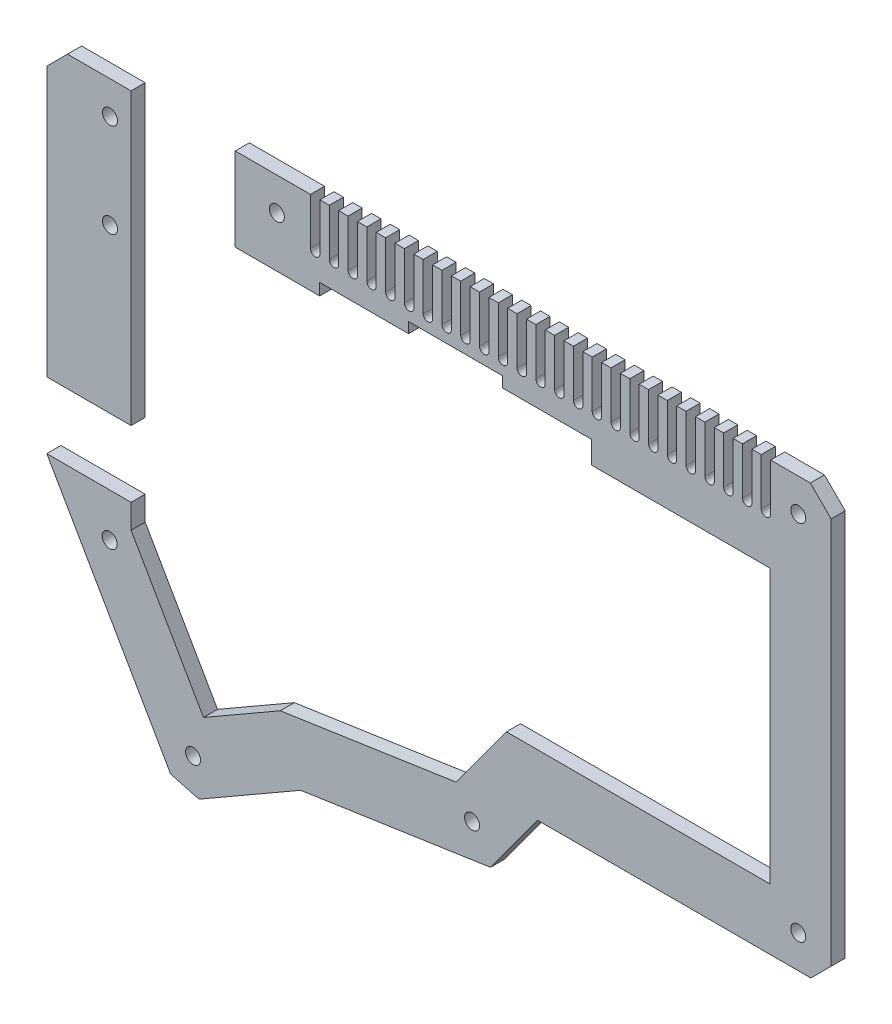
SolidWorks part; units mm, degrees
ref_plane "Plan de face" through (0, 0, 0) normal (0, 0, 1) x (1, 0, 0)
ref_plane "Plan de dessus" through (0, 0, 0) normal (0, 1, 0) x (1, 0, 0)
ref_plane "Plan de droite" through (0, 0, 0) normal (1, 0, 0) x (0, 0, -1)
sketch "Esquisse1" plane through (0, 0, 0) normal (0, 0, 1) x (1, 0, 0)
  line L0 (-117.3419, -15.4198) -> (-103.3409, -15.4198) construction
  line L1 (-103.3409, -15.4198) -> (-103.3409, -29.4208) construction
  line L2 (-103.3409, -29.4208) -> (-117.3419, -29.4208) construction
  line L3 (-117.3419, -29.4208) -> (-117.3419, -15.4198) construction
  line L4 (-98.3406, -27.0457) -> (-98.3406, -13.0447) construction
  line L5 (-98.3406, -13.0447) -> (-84.3396, -13.0447) construction
  line L6 (-84.3396, -13.0447) -> (-84.3396, -27.0457) construction
  line L7 (-84.3396, -27.0457) -> (-98.3406, -27.0457) construction
  line L8 (-79.3392, -24.6705) -> (-79.3392, -10.6695) construction
  line L9 (-79.3392, -10.6695) -> (-65.3382, -10.6695) construction
  line L10 (-65.3382, -10.6695) -> (-65.3382, -24.6705) construction
  line L11 (-65.3382, -24.6705) -> (-79.3392, -24.6705) construction
  line L12 (-60.3379, -27.0457) -> (-60.3379, -13.0447) construction
  line L13 (-60.3379, -13.0447) -> (-46.3369, -13.0447) construction
  line L14 (-46.3369, -13.0447) -> (-46.3369, -27.0457) construction
  line L15 (-46.3369, -27.0457) -> (-60.3379, -27.0457) construction
  line L16 (-41.3365, -31.796) -> (-41.3365, -17.795) construction
  line L17 (-41.3365, -17.795) -> (-27.3355, -17.795) construction
  line L18 (-27.3355, -17.795) -> (-27.3355, -31.796) construction
  line L19 (-27.3355, -31.796) -> (-41.3365, -31.796) construction
  line L20 (-22.3347, -31.796) -> (-22.3347, -17.795) construction
  line L21 (-22.3347, -17.795) -> (-8.3337, -17.795) construction
  line L22 (-8.3337, -17.795) -> (-8.3337, -31.796) construction
  line L23 (-8.3337, -31.796) -> (-22.3347, -31.796) construction
  line L24 (-117.3419, -34.4212) -> (-103.3409, -34.4212) construction
  line L25 (-103.3409, -34.4212) -> (-103.3409, -48.4222) construction
  line L26 (-103.3409, -48.4222) -> (-117.3419, -48.4222) construction
  line L27 (-117.3419, -48.4222) -> (-117.3419, -34.4212) construction
  line L28 (-98.3406, -32.046) -> (-84.3396, -32.046) construction
  line L29 (-84.3396, -32.046) -> (-84.3396, -46.047) construction
  line L30 (-84.3396, -46.047) -> (-98.3406, -46.047) construction
  line L31 (-98.3406, -46.047) -> (-98.3406, -32.046) construction
  line L32 (-79.3392, -29.6709) -> (-65.3382, -29.6709) construction
  line L33 (-65.3382, -29.6709) -> (-65.3382, -43.6718) construction
  line L34 (-65.3382, -43.6718) -> (-79.3392, -43.6718) construction
  line L35 (-79.3392, -43.6718) -> (-79.3392, -29.6709) construction
  line L36 (-60.3379, -32.046) -> (-46.3369, -32.046) construction
  line L37 (-46.3369, -32.046) -> (-46.3369, -46.047) construction
  line L38 (-46.3369, -46.047) -> (-60.3379, -46.047) construction
  line L39 (-60.3379, -46.047) -> (-60.3379, -32.046) construction
  line L40 (-41.3365, -36.7964) -> (-27.3355, -36.7964) construction
  line L41 (-27.3355, -36.7964) -> (-27.3355, -50.7973) construction
  line L42 (-27.3355, -50.7973) -> (-41.3365, -50.7973) construction
  line L43 (-41.3365, -50.7973) -> (-41.3365, -36.7964) construction
  line L44 (-22.3347, -36.7964) -> (-8.3337, -36.7964) construction
  line L45 (-8.3337, -36.7964) -> (-8.3337, -50.7973) construction
  line L46 (-8.3337, -50.7973) -> (-22.3347, -50.7973) construction
  line L47 (-22.3347, -50.7973) -> (-22.3347, -36.7964) construction
  line L48 (-22.3347, -55.7977) -> (-8.3337, -55.7977) construction
  line L49 (-8.3337, -55.7977) -> (-8.3337, -69.7987) construction
  line L50 (-8.3337, -69.7987) -> (-22.3347, -69.7987) construction
  line L51 (-22.3347, -69.7987) -> (-22.3347, -55.7977) construction
  line L52 (-41.3365, -55.7977) -> (-27.3355, -55.7977) construction
  line L53 (-27.3355, -55.7977) -> (-27.3355, -69.7987) construction
  line L54 (-27.3355, -69.7987) -> (-41.3365, -69.7987) construction
  line L55 (-41.3365, -69.7987) -> (-41.3365, -55.7977) construction
  line L56 (-60.3379, -51.0474) -> (-46.3369, -51.0474) construction
  line L57 (-46.3369, -51.0474) -> (-46.3369, -65.0484) construction
  line L58 (-46.3369, -65.0484) -> (-60.3379, -65.0484) construction
  line L59 (-60.3379, -65.0484) -> (-60.3379, -51.0474) construction
  line L60 (-79.3392, -48.6722) -> (-65.3382, -48.6722) construction
  line L61 (-65.3382, -48.6722) -> (-65.3382, -62.6732) construction
  line L62 (-65.3382, -62.6732) -> (-79.3392, -62.6732) construction
  line L63 (-79.3392, -62.6732) -> (-79.3392, -48.6722) construction
  line L64 (-98.3406, -51.0474) -> (-84.3396, -51.0474) construction
  line L65 (-84.3396, -51.0474) -> (-84.3396, -65.0484) construction
  line L66 (-84.3396, -65.0484) -> (-98.3406, -65.0484) construction
  line L67 (-98.3406, -65.0484) -> (-98.3406, -51.0474) construction
  line L68 (-117.3419, -53.4225) -> (-103.3409, -53.4225) construction
  line L69 (-103.3409, -53.4225) -> (-103.3409, -67.4235) construction
  line L70 (-103.3409, -67.4235) -> (-117.3419, -67.4235) construction
  line L71 (-117.3419, -67.4235) -> (-117.3419, -53.4225) construction
  line L72 (-88.8399, -70.6738) -> (-74.8389, -70.6738) construction
  line L73 (-74.8389, -70.6738) -> (-74.8389, -84.6747) construction
  line L74 (-74.8389, -84.6747) -> (-88.8399, -84.6747) construction
  line L75 (-88.8399, -84.6747) -> (-88.8399, -70.6738) construction
  line L76 (-111.4175, -75.4665) -> (-97.8899, -71.8565) construction
  line L77 (-97.8899, -71.8565) -> (-94.28, -85.3841) construction
  line L78 (-94.28, -85.3841) -> (-107.8075, -88.9941) construction
  line L79 (-107.8075, -88.9941) -> (-111.4175, -75.4665) construction
  line L80 (-134.6581, -81.5997) -> (-122.5281, -74.6075) construction
  line L81 (-122.5281, -74.6075) -> (-115.5359, -86.7375) construction
  line L82 (-115.5359, -86.7375) -> (-127.6659, -93.7297) construction
  line L83 (-127.6659, -93.7297) -> (-134.6581, -81.5997) construction
  line L86 (-6.4297, -71.9336) -> (-62.0853, -71.9336) construction
  line L89 (-72.824, -86.6446) -> (-62.0853, -71.9336) construction
  line L96 (-109.7697, -91.4639) -> (-73.0906, -86.6918) construction
  line L97 (-124.664, -99.8297) -> (-110.3971, -91.5881) construction
  line L98 (-139.9408, -76.5013) -> (-126.7151, -99.4281) construction
  line L99 (-119.8527, -15.5421) -> (-139.6028, -15.5421) construction
  line L100 (-100.8528, -13.2921) -> (-118.8527, -13.2921) construction
  line L101 (-63.8455, -8.5421) -> (-80.8528, -8.5421) construction
  line L102 (-44.8455, -10.792) -> (-62.8485, -10.792) construction
  line L103 (-25.8456, -15.5421) -> (-43.8486, -15.5421) construction
  line L104 (-6.8456, -15.5421) -> (-23.8529, -15.5421) construction
  line L105 (-6.2741, -71.3672) -> (-6.2741, -16.1136) construction
  line L106 (-23.8529, -71.9423) -> (-6.8456, -71.9423) construction
  line L107 (-61.8455, -71.9423) -> (-25.8456, -71.9423) construction
  line L108 (-72.6738, -86.4911) -> (-62.1363, -72.0583) construction
  line L109 (-140.1743, -16.1136) -> (-140.1743, -75.5958) construction
  line L110 (-134.3462, 1.5705) -> (-134.3466, -55.7217) construction
  line L111 (-134.3466, -55.7217) -> (-160.479, -70.8411) construction
  line L112 (-160.479, -70.8411) -> (-133.7613, -117.344) construction
  line L113 (-126.937, -119.1852) -> (-105.0783, -106.604) construction
  line L114 (-105.0783, -106.604) -> (-64.4097, -100.5586) construction
  line L115 (-64.4097, -100.5586) -> (-54.4636, -86.9336) construction
  line L116 (3.6609, -86.9336) -> (-54.4636, -86.9336) construction
  line L117 (8.5703, -82.0242) -> (8.5703, 1.315) construction
  line L129 (8.5703, -86.9336) -> (8.5703, -0.6796) construction
  line L130 (-48.4337, 6.3182) -> (-96.435, 6.3209) construction
  line L131 (-115.3458, 1.5705) -> (-134.3462, 1.5705) construction
  line L132 (-160.479, -3.4295) -> (-160.479, -70.8411) construction
  line L134 (-119.3463, 1.5705) -> (-119.3464, -12.4295)
  line L135 (-119.3466, -64.3728) -> (-135.695, -73.8315) construction
  line L136 (-140.0228, -76.3355) -> (-140.0228, -76.3321)
  line L138 (-160.479, -70.8411) -> (-131.2704, -121.6794) construction
  line L139 (-131.2704, -121.6794) -> (-105.0783, -106.604) construction
  line L140 (-133.7613, -117.344) -> (-126.937, -119.1852) construction
  line L142 (8.5703, 1.315) -> (3.5703, 6.3153) construction
  line L143 (8.5703, -86.9336) -> (-54.4636, -86.9336) construction
  line L144 (8.5703, -82.0242) -> (3.6609, -86.9336) construction
  line L150 (-140.0228, 1.5705) -> (-140.0228, 6.3209) construction
  line L151 (-140.0228, 6.3209) -> (-155.479, 6.3209) construction
  line L152 (-160.479, 1.3209) -> (-160.479, -3.4295) construction
  line L153 (-155.479, 6.3209) -> (-160.479, 1.3209) construction
  line L154 (-103.4315, 5.3209) -> (-118.3463, 5.3209) construction
  line L155 (-146.0924, -79.8227) -> (-128.3223, -110.752) construction
  line L156 (-128.3223, -110.752) -> (-107.7547, -98.9139) construction
  line L157 (-140.0228, -78.3428) -> (-126.1111, -102.5565)
  line L158 (-126.1111, -102.5565) -> (-109.762, -93.1464)
  line L159 (-109.762, -93.1464) -> (-72.2631, -87.5722)
  line L160 (-72.2631, -87.5722) -> (-61.5772, -72.9336)
  line L161 (-5.4297, -72.9336) -> (-61.5772, -72.9336)
  line L162 (-5.4297, -72.9336) -> (-5.4297, -14.6796)
  line L163 (-5.4297, -14.6796) -> (-43.4324, -14.6796)
  line L164 (-43.4324, -14.6796) -> (-43.4324, -9.9293)
  line L165 (-43.4324, -9.9293) -> (-62.4337, -9.9293)
  line L166 (-62.4337, -9.9293) -> (-62.4337, -7.681)
  line L167 (-62.4337, -7.681) -> (-82.435, -7.6799)
  line L168 (-82.435, -7.6799) -> (-82.435, -9.9293)
  line L169 (-82.435, -9.9293) -> (-101.3458, -9.9293)
  line L170 (-101.3458, -9.9293) -> (-101.3458, -12.4295)
  line L171 (-101.3458, -12.4295) -> (-119.3464, -12.4295)
  line L172 (-120.3463, -12.4295) -> (-120.3466, -64.3728) construction
  line L173 (-119.8474, -63.5072) -> (-140.5236, -75.4699) construction
  line L174 (-107.7547, -98.9139) -> (-68.8973, -93.1378) construction
  line L175 (-68.8973, -93.1378) -> (-58.5285, -78.9336) construction
  line L176 (0.5703, -78.9336) -> (-58.5285, -78.9336) construction
  line L177 (0.5703, -78.9336) -> (0.5703, -1.6845) construction
  line L178 (3.1505, 5.3209) -> (-119.3463, 5.3209)
  line L179 (0.5703, -78.9336) -> (0.5703, -14.6796) construction
  line L180 (-146.0228, -76.3355) -> (-146.0228, 1.5705) construction
  line L181 (-140.0228, -76.3355) -> (-140.0228, 1.5705) construction
  line L182 (-135.695, -73.8315) -> (-140.0228, -71.3355) construction
  line L186 (-118.3463, 5.3209) -> (-118.3463, 1.5705) construction
  line L187 (-118.3463, 1.5705) -> (-118.3466, -64.9495) construction
  line L188 (-118.3466, -64.9495) -> (-135.6942, -74.9864) construction
  line L189 (-135.6942, -74.9864) -> (-141.0228, -71.9131) construction
  line L190 (-141.0228, -71.9131) -> (-141.0228, 1.5705) construction
  line L191 (-141.0228, 1.5705) -> (-141.0228, 5.3209) construction
  line L192 (-141.5228, 5.3209) -> (-155.0648, 5.3209)
  line L193 (-155.0648, 5.3209) -> (-159.479, 0.9066)
  line L194 (-159.479, 0.9066) -> (-159.479, -3.4295)
  line L195 (-159.479, -3.4295) -> (-159.479, -70.5743)
  line L196 (-159.479, -70.5743) -> (-133.1007, -116.4865)
  line L197 (-133.1007, -116.4865) -> (-127.0766, -118.1118)
  line L198 (-127.0766, -118.1118) -> (-105.4129, -105.6427)
  line L199 (-105.4129, -105.6427) -> (-64.9706, -99.631)
  line L200 (-64.9706, -99.631) -> (-54.9717, -85.9336)
  line L201 (3.2467, -85.9336) -> (-54.9717, -85.9336)
  line L202 (7.5703, -81.61) -> (3.2467, -85.9336)
  line L203 (7.5703, -81.61) -> (7.5703, 0.9008)
  line L204 (7.5703, 0.9008) -> (3.1505, 5.3209)
  line L206 (-140.0228, -76.3321) -> (-119.3466, -64.3728) construction
  line L207 (-140.0228, -71.3355) -> (-140.0228, 1.5705) construction
  line L208 (-119.3463, 5.3209) -> (-119.3463, 1.5705)
  line L209 (-140.8899, -76.8336) -> (-126.1111, -102.5565) construction
  line L210 (-119.3463, 1.5705) -> (-119.3466, -64.3728) construction
  line L211 (-101.3458, -12.4295) -> (-120.3463, -12.4295) construction
  line L212 (-119.3463, 6.3209) -> (-119.3463, 1.5705) construction
  line L217 (-6.4297, -71.9336) -> (-6.4297, -15.6796) construction
  line L220 (-6.4297, -15.6796) -> (-44.4324, -15.6796) construction
  line L221 (-44.4324, -15.6796) -> (-44.4324, -10.9293) construction
  line L222 (-44.4324, -10.9293) -> (-63.4337, -10.9293) construction
  line L223 (-63.4337, -10.9293) -> (-63.4337, -8.681) construction
  line L224 (-63.4337, -8.681) -> (-81.435, -8.68) construction
  line L225 (-81.435, -8.68) -> (-81.435, -10.9293) construction
  line L226 (-81.435, -10.9293) -> (-100.3458, -10.9293) construction
  line L227 (-100.3458, -10.9293) -> (-100.3458, -13.4295) construction
  line L228 (-100.3458, -13.4295) -> (-119.3463, -13.4295) construction
  line L231 (-119.3463, -13.4295) -> (-119.3466, -64.3728) construction
  line L232 (-119.3466, -64.3728) -> (-140.0228, -76.3355) construction
  line L233 (-140.0228, -76.3355) -> (-125.7426, -101.1906) construction
  line L234 (-125.7426, -101.1906) -> (-110.0965, -92.1851) construction
  line L235 (-110.0965, -92.1851) -> (-72.824, -86.6446) construction
  line L237 (7.5703, 0.9008) -> (3.1561, 5.3153) construction
  line L238 (-140.0228, -76.3355) -> (-140.8899, -76.8336) construction
  line L241 (-140.8899, -76.8336) -> (-140.0228, -78.3428)
  line L244 (-140.521, -75.4684) -> (-140.5223, -75.4691)
  line L247 (-141.5228, -75.732) -> (-140.8899, -76.8336)
  line L253 (-140.0228, -75.1802) -> (-140.0228, 5.3209) construction
  line L256 (-146.0228, -1.6779) -> (-146.0228, -21.6805) construction
  line L259 (-141.5228, -75.1802) -> (-141.5228, 5.3209)
  line L262 (-141.5228, -75.1802) -> (-141.5228, -75.732)
  line L265 (-141.0228, 5.3209) -> (-155.0648, 5.3209) construction
  line L271 (-140.521, -75.4684) -> (-141.3881, -75.9666) construction
  line L321 (3.1561, 5.3153) -> (-96.435, 5.3209) construction
  line L328 (-48.4337, 4.0707) -> (-48.4337, 6.3182) construction
  line L329 (-29.4324, 4.0707) -> (-48.4337, 4.0707) construction
  line L330 (-29.4324, -0.6796) -> (-29.4324, 4.0707) construction
  line L331 (8.5703, -0.6796) -> (-29.4324, -0.6796) construction
  line L332 (-115.3458, 4.0707) -> (-115.3458, 1.5705) construction
  line L333 (-96.435, 4.0707) -> (-115.3458, 4.0707) construction
  line L334 (-96.435, 6.3209) -> (-96.435, 4.0707) construction
  line L368 (-103.4315, 5.3209) -> (-96.435, 5.3209) construction
  line L386 (3.5703, 6.3153) -> (-96.435, 6.3209) construction
  line L438 (-103.4315, 6.3209) -> (-96.435, 6.3209) construction
  line L439 (-103.4315, 6.3209) -> (-119.3463, 6.3209) construction
  circle A2 centre (0.5703, -1.6845) radius 1.6
  circle A3 centre (0.5703, -1.6845) radius 3 construction
  circle A4 centre (-110.4876, -1.6784) radius 1.6
  circle A5 centre (0.5703, -78.9336) radius 1.6
  circle A6 centre (-68.8973, -93.1378) radius 1.6
  circle A7 centre (-128.3223, -110.752) radius 1.6
  circle A8 centre (-146.0924, -79.8227) radius 1.6
  circle A9 centre (-146.0228, -1.6779) radius 1.6
  circle A10 centre (-110.4876, -1.6784) radius 3 construction
  circle A11 centre (-146.0228, -1.6779) radius 3 construction
  circle A12 centre (-146.0924, -79.8227) radius 3 construction
  circle A13 centre (-128.3223, -110.752) radius 3 construction
  circle A14 centre (-68.8973, -93.1378) radius 3 construction
  circle A15 centre (0.5703, -78.9336) radius 3 construction
  circle A16 centre (-146.0228, -21.6805) radius 1.6
  point P138 (-160.479, 1.5705)
  point P139 (8.5703, 6.315)
  point P150 (-160.479, 6.3209)
  dimension "D3" = 3.2
  dimension "D4" = 6
  dimension "D6" = 3.2
  dimension "D7" = 3.2
  dimension "D8" = 3.2
  dimension "D9" = 3.2
  dimension "D10" = 3.2
  dimension "D15" = 3.2
  dimension "D2" = 1
  dimension "D1" = 15
  dimension "D5" = 1
  dimension "D13" = 6
  dimension "D16" = 1.5
extrude "Boss.-Extru.1" add sketch "Esquisse1" along normal blind 3
sketch "Esquisse2" plane through (0, 0, 3) normal (0, 0, 1) x (1, 0, 0)
  line L0 (7.5703, -7.8762) -> (-6.3155, -7.8762) construction
  line L1 (7.5703, -81.61) -> (7.5703, 0.9008) construction
  line L2 (-6.3155, 5.3209) -> (-6.3155, -4.6791) construction
  line L3 (3.1505, 5.3209) -> (-119.3463, 5.3209) construction
  line L4 (-6.3155, 8.6159) -> (-6.3155, -4.6791) construction
  line L5 (-5.3155, 8.6159) -> (-5.3155, -4.6791)
  line L6 (-7.3155, 8.6159) -> (-7.3155, -4.6791)
  line L7 (-10.3155, 8.6159) -> (-10.3155, -4.6791) construction
  line L8 (-9.3155, 8.6159) -> (-9.3155, -4.6791)
  line L9 (-11.3155, 8.6159) -> (-11.3155, -4.6791)
  line L10 (-14.3155, 8.6159) -> (-14.3155, -4.6791) construction
  line L11 (-13.3155, 8.6159) -> (-13.3155, -4.6791)
  line L12 (-15.3155, 8.6159) -> (-15.3155, -4.6791)
  line L13 (-18.3155, 8.6159) -> (-18.3155, -4.6791) construction
  line L14 (-17.3155, 8.6159) -> (-17.3155, -4.6791)
  line L15 (-19.3155, 8.6159) -> (-19.3155, -4.6791)
  line L16 (-22.3155, 8.6159) -> (-22.3155, -4.6791) construction
  line L17 (-21.3155, 8.6159) -> (-21.3155, -4.6791)
  line L18 (-23.3155, 8.6159) -> (-23.3155, -4.6791)
  line L19 (-26.3155, 8.6159) -> (-26.3155, -4.6791) construction
  line L20 (-25.3155, 8.6159) -> (-25.3155, -4.6791)
  line L21 (-27.3155, 8.6159) -> (-27.3155, -4.6791)
  line L22 (-30.3155, 8.6159) -> (-30.3155, -4.6791) construction
  line L23 (-29.3155, 8.6159) -> (-29.3155, -4.6791)
  line L24 (-31.3155, 8.6159) -> (-31.3155, -4.6791)
  line L25 (-34.3155, 8.6159) -> (-34.3155, -4.6791) construction
  line L26 (-33.3155, 8.6159) -> (-33.3155, -4.6791)
  line L27 (-35.3155, 8.6159) -> (-35.3155, -4.6791)
  line L28 (-38.3155, 8.6159) -> (-38.3155, -4.6791) construction
  line L29 (-37.3155, 8.6159) -> (-37.3155, -4.6791)
  line L30 (-39.3155, 8.6159) -> (-39.3155, -4.6791)
  line L31 (-42.3155, 8.6159) -> (-42.3155, -4.6791) construction
  line L32 (-41.3155, 8.6159) -> (-41.3155, -4.6791)
  line L33 (-43.3155, 8.6159) -> (-43.3155, -4.6791)
  line L34 (-46.3155, 8.6159) -> (-46.3155, -4.6791) construction
  line L35 (-45.3155, 8.6159) -> (-45.3155, -4.6791)
  line L36 (-47.3155, 8.6159) -> (-47.3155, -4.6791)
  line L37 (-50.3155, 8.6159) -> (-50.3155, -4.6791) construction
  line L38 (-49.3155, 8.6159) -> (-49.3155, -4.6791)
  line L39 (-51.3155, 8.6159) -> (-51.3155, -4.6791)
  line L40 (-54.3155, 8.6159) -> (-54.3155, -4.6791) construction
  line L41 (-53.3155, 8.6159) -> (-53.3155, -4.6791)
  line L42 (-55.3155, 8.6159) -> (-55.3155, -4.6791)
  line L43 (-58.3155, 8.6159) -> (-58.3155, -4.6791) construction
  line L44 (-57.3155, 8.6159) -> (-57.3155, -4.6791)
  line L45 (-59.3155, 8.6159) -> (-59.3155, -4.6791)
  line L46 (-62.3155, 8.6159) -> (-62.3155, -4.6791) construction
  line L47 (-61.3155, 8.6159) -> (-61.3155, -4.6791)
  line L48 (-63.3155, 8.6159) -> (-63.3155, -4.6791)
  line L49 (-66.3155, 8.6159) -> (-66.3155, -4.6791) construction
  line L50 (-65.3155, 8.6159) -> (-65.3155, -4.6791)
  line L51 (-67.3155, 8.6159) -> (-67.3155, -4.6791)
  line L52 (-70.3155, 8.6159) -> (-70.3155, -4.6791) construction
  line L53 (-69.3155, 8.6159) -> (-69.3155, -4.6791)
  line L54 (-71.3155, 8.6159) -> (-71.3155, -4.6791)
  line L55 (-74.3155, 8.6159) -> (-74.3155, -4.6791) construction
  line L56 (-73.3155, 8.6159) -> (-73.3155, -4.6791)
  line L57 (-75.3155, 8.6159) -> (-75.3155, -4.6791)
  line L58 (-78.3155, 8.6159) -> (-78.3155, -4.6791) construction
  line L59 (-77.3155, 8.6159) -> (-77.3155, -4.6791)
  line L60 (-79.3155, 8.6159) -> (-79.3155, -4.6791)
  line L61 (-82.3155, 8.6159) -> (-82.3155, -4.6791) construction
  line L62 (-81.3155, 8.6159) -> (-81.3155, -4.6791)
  line L63 (-83.3155, 8.6159) -> (-83.3155, -4.6791)
  line L64 (-86.3155, 8.6159) -> (-86.3155, -4.6791) construction
  line L65 (-85.3155, 8.6159) -> (-85.3155, -4.6791)
  line L66 (-87.3155, 8.6159) -> (-87.3155, -4.6791)
  line L67 (-90.3155, 8.6159) -> (-90.3155, -4.6791) construction
  line L68 (-89.3155, 8.6159) -> (-89.3155, -4.6791)
  line L69 (-91.3155, 8.6159) -> (-91.3155, -4.6791)
  line L70 (-94.3155, 8.6159) -> (-94.3155, -4.6791) construction
  line L71 (-93.3155, 8.6159) -> (-93.3155, -4.6791)
  line L72 (-95.3155, 8.6159) -> (-95.3155, -4.6791)
  line L73 (-98.3155, 8.6159) -> (-98.3155, -4.6791) construction
  line L74 (-97.3155, 8.6159) -> (-97.3155, -4.6791)
  line L75 (-99.3155, 8.6159) -> (-99.3155, -4.6791)
  line L76 (-102.3155, 8.6159) -> (-102.3155, -4.6791) construction
  line L77 (-101.3155, 8.6159) -> (-101.3155, -4.6791)
  line L78 (-103.3155, 8.6159) -> (-103.3155, -4.6791)
  arc A0 (-5.3155, 8.6159) -> (-7.3155, 8.6159) centre (-6.3155, 8.6159) ccw
  arc A1 (-7.3155, -4.6791) -> (-5.3155, -4.6791) centre (-6.3155, -4.6791) ccw
  arc A2 (-9.3155, 8.6159) -> (-11.3155, 8.6159) centre (-10.3155, 8.6159) ccw
  arc A3 (-11.3155, -4.6791) -> (-9.3155, -4.6791) centre (-10.3155, -4.6791) ccw
  arc A4 (-13.3155, 8.6159) -> (-15.3155, 8.6159) centre (-14.3155, 8.6159) ccw
  arc A5 (-15.3155, -4.6791) -> (-13.3155, -4.6791) centre (-14.3155, -4.6791) ccw
  arc A6 (-17.3155, 8.6159) -> (-19.3155, 8.6159) centre (-18.3155, 8.6159) ccw
  arc A7 (-19.3155, -4.6791) -> (-17.3155, -4.6791) centre (-18.3155, -4.6791) ccw
  arc A8 (-21.3155, 8.6159) -> (-23.3155, 8.6159) centre (-22.3155, 8.6159) ccw
  arc A9 (-23.3155, -4.6791) -> (-21.3155, -4.6791) centre (-22.3155, -4.6791) ccw
  arc A10 (-25.3155, 8.6159) -> (-27.3155, 8.6159) centre (-26.3155, 8.6159) ccw
  arc A11 (-27.3155, -4.6791) -> (-25.3155, -4.6791) centre (-26.3155, -4.6791) ccw
  arc A12 (-29.3155, 8.6159) -> (-31.3155, 8.6159) centre (-30.3155, 8.6159) ccw
  arc A13 (-31.3155, -4.6791) -> (-29.3155, -4.6791) centre (-30.3155, -4.6791) ccw
  arc A14 (-33.3155, 8.6159) -> (-35.3155, 8.6159) centre (-34.3155, 8.6159) ccw
  arc A15 (-35.3155, -4.6791) -> (-33.3155, -4.6791) centre (-34.3155, -4.6791) ccw
  arc A16 (-37.3155, 8.6159) -> (-39.3155, 8.6159) centre (-38.3155, 8.6159) ccw
  arc A17 (-39.3155, -4.6791) -> (-37.3155, -4.6791) centre (-38.3155, -4.6791) ccw
  arc A18 (-41.3155, 8.6159) -> (-43.3155, 8.6159) centre (-42.3155, 8.6159) ccw
  arc A19 (-43.3155, -4.6791) -> (-41.3155, -4.6791) centre (-42.3155, -4.6791) ccw
  arc A20 (-45.3155, 8.6159) -> (-47.3155, 8.6159) centre (-46.3155, 8.6159) ccw
  arc A21 (-47.3155, -4.6791) -> (-45.3155, -4.6791) centre (-46.3155, -4.6791) ccw
  arc A22 (-49.3155, 8.6159) -> (-51.3155, 8.6159) centre (-50.3155, 8.6159) ccw
  arc A23 (-51.3155, -4.6791) -> (-49.3155, -4.6791) centre (-50.3155, -4.6791) ccw
  arc A24 (-53.3155, 8.6159) -> (-55.3155, 8.6159) centre (-54.3155, 8.6159) ccw
  arc A25 (-55.3155, -4.6791) -> (-53.3155, -4.6791) centre (-54.3155, -4.6791) ccw
  arc A26 (-57.3155, 8.6159) -> (-59.3155, 8.6159) centre (-58.3155, 8.6159) ccw
  arc A27 (-59.3155, -4.6791) -> (-57.3155, -4.6791) centre (-58.3155, -4.6791) ccw
  arc A28 (-61.3155, 8.6159) -> (-63.3155, 8.6159) centre (-62.3155, 8.6159) ccw
  arc A29 (-63.3155, -4.6791) -> (-61.3155, -4.6791) centre (-62.3155, -4.6791) ccw
  arc A30 (-65.3155, 8.6159) -> (-67.3155, 8.6159) centre (-66.3155, 8.6159) ccw
  arc A31 (-67.3155, -4.6791) -> (-65.3155, -4.6791) centre (-66.3155, -4.6791) ccw
  arc A32 (-69.3155, 8.6159) -> (-71.3155, 8.6159) centre (-70.3155, 8.6159) ccw
  arc A33 (-71.3155, -4.6791) -> (-69.3155, -4.6791) centre (-70.3155, -4.6791) ccw
  arc A34 (-73.3155, 8.6159) -> (-75.3155, 8.6159) centre (-74.3155, 8.6159) ccw
  arc A35 (-75.3155, -4.6791) -> (-73.3155, -4.6791) centre (-74.3155, -4.6791) ccw
  arc A36 (-77.3155, 8.6159) -> (-79.3155, 8.6159) centre (-78.3155, 8.6159) ccw
  arc A37 (-79.3155, -4.6791) -> (-77.3155, -4.6791) centre (-78.3155, -4.6791) ccw
  arc A38 (-81.3155, 8.6159) -> (-83.3155, 8.6159) centre (-82.3155, 8.6159) ccw
  arc A39 (-83.3155, -4.6791) -> (-81.3155, -4.6791) centre (-82.3155, -4.6791) ccw
  arc A40 (-85.3155, 8.6159) -> (-87.3155, 8.6159) centre (-86.3155, 8.6159) ccw
  arc A41 (-87.3155, -4.6791) -> (-85.3155, -4.6791) centre (-86.3155, -4.6791) ccw
  arc A42 (-89.3155, 8.6159) -> (-91.3155, 8.6159) centre (-90.3155, 8.6159) ccw
  arc A43 (-91.3155, -4.6791) -> (-89.3155, -4.6791) centre (-90.3155, -4.6791) ccw
  arc A44 (-93.3155, 8.6159) -> (-95.3155, 8.6159) centre (-94.3155, 8.6159) ccw
  arc A45 (-95.3155, -4.6791) -> (-93.3155, -4.6791) centre (-94.3155, -4.6791) ccw
  arc A46 (-97.3155, 8.6159) -> (-99.3155, 8.6159) centre (-98.3155, 8.6159) ccw
  arc A47 (-99.3155, -4.6791) -> (-97.3155, -4.6791) centre (-98.3155, -4.6791) ccw
  arc A48 (-101.3155, 8.6159) -> (-103.3155, 8.6159) centre (-102.3155, 8.6159) ccw
  arc A49 (-103.3155, -4.6791) -> (-101.3155, -4.6791) centre (-102.3155, -4.6791) ccw
  point P9 (-6.3155, 1.9684)
  point P17 (-10.3155, 1.9684)
  point P24 (-14.3155, 1.9684)
  point P31 (-18.3155, 1.9684)
  point P38 (-22.3155, 1.9684)
  point P45 (-26.3155, 1.9684)
  point P52 (-30.3155, 1.9684)
  point P59 (-34.3155, 1.9684)
  point P66 (-38.3155, 1.9684)
  point P73 (-42.3155, 1.9684)
  point P80 (-46.3155, 1.9684)
  point P87 (-50.3155, 1.9684)
  point P94 (-54.3155, 1.9684)
  point P101 (-58.3155, 1.9684)
  point P108 (-62.3155, 1.9684)
  point P115 (-66.3155, 1.9684)
  point P122 (-70.3155, 1.9684)
  point P129 (-74.3155, 1.9684)
  point P136 (-78.3155, 1.9684)
  point P143 (-82.3155, 1.9684)
  point P150 (-86.3155, 1.9684)
  point P157 (-90.3155, 1.9684)
  point P164 (-94.3155, 1.9684)
  point P171 (-98.3155, 1.9684)
  point P178 (-102.3155, 1.9684)
  dimension "D1" = 25
extrude "Enlèv. mat.-Extru.1" cut sketch "Esquisse2" against normal blind 10
sketch "Esquisse3" plane through (0, 0, 3) normal (0, 0, 1) x (1, 0, 0)
  line L0 (-159.479, -70.5743) -> (-140.0228, -70.5743)
  line L1 (-140.0228, -75.1802) -> (-140.0228, 5.3209) construction
  line L2 (-117.3419, -53.4225) -> (-140.0228, -53.4225) construction
  line L3 (-140.0228, -53.4225) -> (-140.0228, -56.4239) construction
  line L4 (-140.0228, -70.5743) -> (-140.0228, -56.4239)
  line L5 (-140.0228, -56.4239) -> (-159.479, -56.4239)
  line L6 (-159.479, -3.4295) -> (-159.479, -70.5743) construction
  line L7 (-159.479, -56.4239) -> (-159.479, -70.5743)
extrude "Enlèv. mat.-Extru.2" cut sketch "Esquisse3" against normal blind 10
sketch "Esquisse4" plane through (0, 0, 3) normal (0, 0, 1) x (1, 0, 0)
  line L5 (-159.479, -56.4239) -> (-141.5228, -56.4239)
  line L6 (-141.5228, -56.4239) -> (-141.5228, 5.3209)
  line L7 (-141.5228, 5.3209) -> (-155.0648, 5.3209)
  line L8 (-155.0648, 5.3209) -> (-159.479, 0.9066)
  line L9 (-159.479, 0.9066) -> (-159.479, -56.4239)
  line L10 (-159.479, -56.4239) -> (-141.5228, -56.4239)
  line L11 (-141.5228, -56.4239) -> (-141.5228, 5.3209)
  line L12 (-141.5228, 5.3209) -> (-155.0648, 5.3209)
  line L13 (-155.0648, 5.3209) -> (-159.479, 0.9066)
  line L14 (-159.479, 0.9066) -> (-159.479, -56.4239)
  line L104 (-141.5228, -70.5743) -> (-159.479, -70.5743)
  line L105 (-159.479, -70.5743) -> (-133.1007, -116.4865)
  line L106 (-133.1007, -116.4865) -> (-127.0766, -118.1118)
  line L107 (-127.0766, -118.1118) -> (-105.4129, -105.6427)
  line L108 (-105.4129, -105.6427) -> (-64.9706, -99.631)
  line L109 (-64.9706, -99.631) -> (-54.9717, -85.9336)
  line L110 (-54.9717, -85.9336) -> (3.2467, -85.9336)
  line L111 (3.2467, -85.9336) -> (7.5703, -81.61)
  line L112 (7.5703, -81.61) -> (7.5703, 0.9008)
  line L113 (7.5703, 0.9008) -> (3.1505, 5.3209)
  line L114 (3.1505, 5.3209) -> (-5.3155, 5.3209)
  line L115 (-5.3155, 5.3209) -> (-5.3155, -4.6791)
  line L116 (-7.3155, -4.6791) -> (-7.3155, 5.3209)
  line L117 (-7.3155, 5.3209) -> (-9.3155, 5.3209)
  line L118 (-9.3155, 5.3209) -> (-9.3155, -4.6791)
  line L119 (-11.3155, -4.6791) -> (-11.3155, 5.3209)
  line L120 (-11.3155, 5.3209) -> (-13.3155, 5.3209)
  line L121 (-13.3155, 5.3209) -> (-13.3155, -4.6791)
  line L122 (-15.3155, -4.6791) -> (-15.3155, 5.3209)
  line L123 (-15.3155, 5.3209) -> (-17.3155, 5.3209)
  line L124 (-17.3155, 5.3209) -> (-17.3155, -4.6791)
  line L125 (-19.3155, -4.6791) -> (-19.3155, 5.3209)
  line L126 (-19.3155, 5.3209) -> (-21.3155, 5.3209)
  line L127 (-21.3155, 5.3209) -> (-21.3155, -4.6791)
  line L128 (-23.3155, -4.6791) -> (-23.3155, 5.3209)
  line L129 (-23.3155, 5.3209) -> (-25.3155, 5.3209)
  line L130 (-25.3155, 5.3209) -> (-25.3155, -4.6791)
  line L131 (-27.3155, -4.6791) -> (-27.3155, 5.3209)
  line L132 (-27.3155, 5.3209) -> (-29.3155, 5.3209)
  line L133 (-29.3155, 5.3209) -> (-29.3155, -4.6791)
  line L134 (-31.3155, -4.6791) -> (-31.3155, 5.3209)
  line L135 (-31.3155, 5.3209) -> (-33.3155, 5.3209)
  line L136 (-33.3155, 5.3209) -> (-33.3155, -4.6791)
  line L137 (-35.3155, -4.6791) -> (-35.3155, 5.3209)
  line L138 (-35.3155, 5.3209) -> (-37.3155, 5.3209)
  line L139 (-37.3155, 5.3209) -> (-37.3155, -4.6791)
  line L140 (-39.3155, -4.6791) -> (-39.3155, 5.3209)
  line L141 (-39.3155, 5.3209) -> (-41.3155, 5.3209)
  line L142 (-41.3155, 5.3209) -> (-41.3155, -4.6791)
  line L143 (-43.3155, -4.6791) -> (-43.3155, 5.3209)
  line L144 (-43.3155, 5.3209) -> (-45.3155, 5.3209)
  line L145 (-45.3155, 5.3209) -> (-45.3155, -4.6791)
  line L146 (-47.3155, -4.6791) -> (-47.3155, 5.3209)
  line L147 (-47.3155, 5.3209) -> (-49.3155, 5.3209)
  line L148 (-49.3155, 5.3209) -> (-49.3155, -4.6791)
  line L149 (-51.3155, -4.6791) -> (-51.3155, 5.3209)
  line L150 (-51.3155, 5.3209) -> (-53.3155, 5.3209)
  line L151 (-53.3155, 5.3209) -> (-53.3155, -4.6791)
  line L152 (-55.3155, -4.6791) -> (-55.3155, 5.3209)
  line L153 (-55.3155, 5.3209) -> (-57.3155, 5.3209)
  line L154 (-57.3155, 5.3209) -> (-57.3155, -4.6791)
  line L155 (-59.3155, -4.6791) -> (-59.3155, 5.3209)
  line L156 (-59.3155, 5.3209) -> (-61.3155, 5.3209)
  line L157 (-61.3155, 5.3209) -> (-61.3155, -4.6791)
  line L158 (-63.3155, -4.6791) -> (-63.3155, 5.3209)
  line L159 (-63.3155, 5.3209) -> (-65.3155, 5.3209)
  line L160 (-65.3155, 5.3209) -> (-65.3155, -4.6791)
  line L161 (-67.3155, -4.6791) -> (-67.3155, 5.3209)
  line L162 (-67.3155, 5.3209) -> (-69.3155, 5.3209)
  line L163 (-69.3155, 5.3209) -> (-69.3155, -4.6791)
  line L164 (-71.3155, -4.6791) -> (-71.3155, 5.3209)
  line L165 (-71.3155, 5.3209) -> (-73.3155, 5.3209)
  line L166 (-73.3155, 5.3209) -> (-73.3155, -4.6791)
  line L167 (-75.3155, -4.6791) -> (-75.3155, 5.3209)
  line L168 (-75.3155, 5.3209) -> (-77.3155, 5.3209)
  line L169 (-77.3155, 5.3209) -> (-77.3155, -4.6791)
  line L170 (-79.3155, -4.6791) -> (-79.3155, 5.3209)
  line L171 (-79.3155, 5.3209) -> (-81.3155, 5.3209)
  line L172 (-81.3155, 5.3209) -> (-81.3155, -4.6791)
  line L173 (-83.3155, -4.6791) -> (-83.3155, 5.3209)
  line L174 (-83.3155, 5.3209) -> (-85.3155, 5.3209)
  line L175 (-85.3155, 5.3209) -> (-85.3155, -4.6791)
  line L176 (-87.3155, -4.6791) -> (-87.3155, 5.3209)
  line L177 (-87.3155, 5.3209) -> (-89.3155, 5.3209)
  line L178 (-89.3155, 5.3209) -> (-89.3155, -4.6791)
  line L179 (-91.3155, -4.6791) -> (-91.3155, 5.3209)
  line L180 (-91.3155, 5.3209) -> (-93.3155, 5.3209)
  line L181 (-93.3155, 5.3209) -> (-93.3155, -4.6791)
  line L182 (-95.3155, -4.6791) -> (-95.3155, 5.3209)
  line L183 (-95.3155, 5.3209) -> (-97.3155, 5.3209)
  line L184 (-97.3155, 5.3209) -> (-97.3155, -4.6791)
  line L185 (-99.3155, -4.6791) -> (-99.3155, 5.3209)
  line L186 (-99.3155, 5.3209) -> (-101.3155, 5.3209)
  line L187 (-101.3155, 5.3209) -> (-101.3155, -4.6791)
  line L188 (-103.3155, -4.6791) -> (-103.3155, 5.3209)
  line L189 (-103.3155, 5.3209) -> (-119.3463, 5.3209)
  line L190 (-119.3463, 5.3209) -> (-119.3463, 1.5705)
  line L191 (-119.3463, 1.5705) -> (-119.3464, -12.4295)
  line L192 (-119.3464, -12.4295) -> (-101.3458, -12.4295)
  line L193 (-101.3458, -12.4295) -> (-101.3458, -9.9293)
  line L194 (-101.3458, -9.9293) -> (-82.435, -9.9293)
  line L195 (-82.435, -9.9293) -> (-82.435, -7.6799)
  line L196 (-82.435, -7.6799) -> (-62.4337, -7.681)
  line L197 (-62.4337, -7.681) -> (-62.4337, -9.9293)
  line L198 (-62.4337, -9.9293) -> (-43.4324, -9.9293)
  line L199 (-43.4324, -9.9293) -> (-43.4324, -14.6796)
  line L200 (-43.4324, -14.6796) -> (-5.4297, -14.6796)
  line L201 (-5.4297, -14.6796) -> (-5.4297, -72.9336)
  line L202 (-5.4297, -72.9336) -> (-61.5772, -72.9336)
  line L203 (-61.5772, -72.9336) -> (-72.2631, -87.5722)
  line L204 (-72.2631, -87.5722) -> (-109.762, -93.1464)
  line L205 (-109.762, -93.1464) -> (-126.1111, -102.5565)
  line L206 (-126.1111, -102.5565) -> (-141.5228, -75.732)
  line L207 (-141.5228, -75.732) -> (-141.5228, -70.5743)
  line L208 (-141.5228, -70.5743) -> (-159.479, -70.5743)
  line L209 (-159.479, -70.5743) -> (-133.1007, -116.4865)
  line L210 (-133.1007, -116.4865) -> (-127.0766, -118.1118)
  line L211 (-127.0766, -118.1118) -> (-105.4129, -105.6427)
  line L212 (-105.4129, -105.6427) -> (-64.9706, -99.631)
  line L213 (-64.9706, -99.631) -> (-54.9717, -85.9336)
  line L214 (-54.9717, -85.9336) -> (3.2467, -85.9336)
  line L215 (3.2467, -85.9336) -> (7.5703, -81.61)
  line L216 (7.5703, -81.61) -> (7.5703, 0.9008)
  line L217 (7.5703, 0.9008) -> (3.1505, 5.3209)
  line L218 (3.1505, 5.3209) -> (-5.3155, 5.3209)
  line L219 (-5.3155, 5.3209) -> (-5.3155, -4.6791)
  line L220 (-7.3155, -4.6791) -> (-7.3155, 5.3209)
  line L221 (-7.3155, 5.3209) -> (-9.3155, 5.3209)
  line L222 (-9.3155, 5.3209) -> (-9.3155, -4.6791)
  line L223 (-11.3155, -4.6791) -> (-11.3155, 5.3209)
  line L224 (-11.3155, 5.3209) -> (-13.3155, 5.3209)
  line L225 (-13.3155, 5.3209) -> (-13.3155, -4.6791)
  line L226 (-15.3155, -4.6791) -> (-15.3155, 5.3209)
  line L227 (-15.3155, 5.3209) -> (-17.3155, 5.3209)
  line L228 (-17.3155, 5.3209) -> (-17.3155, -4.6791)
  line L229 (-19.3155, -4.6791) -> (-19.3155, 5.3209)
  line L230 (-19.3155, 5.3209) -> (-21.3155, 5.3209)
  line L231 (-21.3155, 5.3209) -> (-21.3155, -4.6791)
  line L232 (-23.3155, -4.6791) -> (-23.3155, 5.3209)
  line L233 (-23.3155, 5.3209) -> (-25.3155, 5.3209)
  line L234 (-25.3155, 5.3209) -> (-25.3155, -4.6791)
  line L235 (-27.3155, -4.6791) -> (-27.3155, 5.3209)
  line L236 (-27.3155, 5.3209) -> (-29.3155, 5.3209)
  line L237 (-29.3155, 5.3209) -> (-29.3155, -4.6791)
  line L238 (-31.3155, -4.6791) -> (-31.3155, 5.3209)
  line L239 (-31.3155, 5.3209) -> (-33.3155, 5.3209)
  line L240 (-33.3155, 5.3209) -> (-33.3155, -4.6791)
  line L241 (-35.3155, -4.6791) -> (-35.3155, 5.3209)
  line L242 (-35.3155, 5.3209) -> (-37.3155, 5.3209)
  line L243 (-37.3155, 5.3209) -> (-37.3155, -4.6791)
  line L244 (-39.3155, -4.6791) -> (-39.3155, 5.3209)
  line L245 (-39.3155, 5.3209) -> (-41.3155, 5.3209)
  line L246 (-41.3155, 5.3209) -> (-41.3155, -4.6791)
  line L247 (-43.3155, -4.6791) -> (-43.3155, 5.3209)
  line L248 (-43.3155, 5.3209) -> (-45.3155, 5.3209)
  line L249 (-45.3155, 5.3209) -> (-45.3155, -4.6791)
  line L250 (-47.3155, -4.6791) -> (-47.3155, 5.3209)
  line L251 (-47.3155, 5.3209) -> (-49.3155, 5.3209)
  line L252 (-49.3155, 5.3209) -> (-49.3155, -4.6791)
  line L253 (-51.3155, -4.6791) -> (-51.3155, 5.3209)
  line L254 (-51.3155, 5.3209) -> (-53.3155, 5.3209)
  line L255 (-53.3155, 5.3209) -> (-53.3155, -4.6791)
  line L256 (-55.3155, -4.6791) -> (-55.3155, 5.3209)
  line L257 (-55.3155, 5.3209) -> (-57.3155, 5.3209)
  line L258 (-57.3155, 5.3209) -> (-57.3155, -4.6791)
  line L259 (-59.3155, -4.6791) -> (-59.3155, 5.3209)
  line L260 (-59.3155, 5.3209) -> (-61.3155, 5.3209)
  line L261 (-61.3155, 5.3209) -> (-61.3155, -4.6791)
  line L262 (-63.3155, -4.6791) -> (-63.3155, 5.3209)
  line L263 (-63.3155, 5.3209) -> (-65.3155, 5.3209)
  line L264 (-65.3155, 5.3209) -> (-65.3155, -4.6791)
  line L265 (-67.3155, -4.6791) -> (-67.3155, 5.3209)
  line L266 (-67.3155, 5.3209) -> (-69.3155, 5.3209)
  line L267 (-69.3155, 5.3209) -> (-69.3155, -4.6791)
  line L268 (-71.3155, -4.6791) -> (-71.3155, 5.3209)
  line L269 (-71.3155, 5.3209) -> (-73.3155, 5.3209)
  line L270 (-73.3155, 5.3209) -> (-73.3155, -4.6791)
  line L271 (-75.3155, -4.6791) -> (-75.3155, 5.3209)
  line L272 (-75.3155, 5.3209) -> (-77.3155, 5.3209)
  line L273 (-77.3155, 5.3209) -> (-77.3155, -4.6791)
  line L274 (-79.3155, -4.6791) -> (-79.3155, 5.3209)
  line L275 (-79.3155, 5.3209) -> (-81.3155, 5.3209)
  line L276 (-81.3155, 5.3209) -> (-81.3155, -4.6791)
  line L277 (-83.3155, -4.6791) -> (-83.3155, 5.3209)
  line L278 (-83.3155, 5.3209) -> (-85.3155, 5.3209)
  line L279 (-85.3155, 5.3209) -> (-85.3155, -4.6791)
  line L280 (-87.3155, -4.6791) -> (-87.3155, 5.3209)
  line L281 (-87.3155, 5.3209) -> (-89.3155, 5.3209)
  line L282 (-89.3155, 5.3209) -> (-89.3155, -4.6791)
  line L283 (-91.3155, -4.6791) -> (-91.3155, 5.3209)
  line L284 (-91.3155, 5.3209) -> (-93.3155, 5.3209)
  line L285 (-93.3155, 5.3209) -> (-93.3155, -4.6791)
  line L286 (-95.3155, -4.6791) -> (-95.3155, 5.3209)
  line L287 (-95.3155, 5.3209) -> (-97.3155, 5.3209)
  line L288 (-97.3155, 5.3209) -> (-97.3155, -4.6791)
  line L289 (-99.3155, -4.6791) -> (-99.3155, 5.3209)
  line L290 (-99.3155, 5.3209) -> (-101.3155, 5.3209)
  line L291 (-101.3155, 5.3209) -> (-101.3155, -4.6791)
  line L292 (-103.3155, -4.6791) -> (-103.3155, 5.3209)
  line L293 (-103.3155, 5.3209) -> (-119.3463, 5.3209)
  line L294 (-119.3463, 5.3209) -> (-119.3463, 1.5705)
  line L295 (-119.3463, 1.5705) -> (-119.3464, -12.4295)
  line L296 (-119.3464, -12.4295) -> (-101.3458, -12.4295)
  line L297 (-101.3458, -12.4295) -> (-101.3458, -9.9293)
  line L298 (-101.3458, -9.9293) -> (-82.435, -9.9293)
  line L299 (-82.435, -9.9293) -> (-82.435, -7.6799)
  line L300 (-82.435, -7.6799) -> (-62.4337, -7.681)
  line L301 (-62.4337, -7.681) -> (-62.4337, -9.9293)
  line L302 (-62.4337, -9.9293) -> (-43.4324, -9.9293)
  line L303 (-43.4324, -9.9293) -> (-43.4324, -14.6796)
  line L304 (-43.4324, -14.6796) -> (-5.4297, -14.6796)
  line L305 (-5.4297, -14.6796) -> (-5.4297, -72.9336)
  line L306 (-5.4297, -72.9336) -> (-61.5772, -72.9336)
  line L307 (-61.5772, -72.9336) -> (-72.2631, -87.5722)
  line L308 (-72.2631, -87.5722) -> (-109.762, -93.1464)
  line L309 (-109.762, -93.1464) -> (-126.1111, -102.5565)
  line L310 (-126.1111, -102.5565) -> (-141.5228, -75.732)
  line L311 (-141.5228, -75.732) -> (-141.5228, -70.5743)
  circle A0 centre (-146.0924, -79.8227) radius 1.6 construction
  circle A1 centre (-128.3223, -110.752) radius 1.6 construction
  circle A2 centre (-68.8973, -93.1378) radius 1.6 construction
  circle A3 centre (0.5703, -78.9336) radius 1.6 construction
  circle A4 centre (0.5703, -1.6845) radius 1.6 construction
  circle A5 centre (-110.4876, -1.6784) radius 1.6 construction
  circle A6 centre (-146.0228, -21.6805) radius 1.6 construction
  circle A7 centre (-146.0228, -1.6779) radius 1.6 construction
  circle A8 centre (-146.0924, -79.8227) radius 1.6
  circle A9 centre (-128.3223, -110.752) radius 1.6
  circle A10 centre (-68.8973, -93.1378) radius 1.6
  circle A11 centre (0.5703, -78.9336) radius 1.6
  circle A12 centre (0.5703, -1.6845) radius 1.6
  circle A13 centre (-110.4876, -1.6784) radius 1.6
  circle A14 centre (-146.0228, -21.6805) radius 1.6
  circle A15 centre (-146.0228, -1.6779) radius 1.6
  arc A25 (-7.3155, -4.6791) -> (-5.3155, -4.6791) centre (-6.3155, -4.6791) ccw
  arc A26 (-11.3155, -4.6791) -> (-9.3155, -4.6791) centre (-10.3155, -4.6791) ccw
  arc A27 (-15.3155, -4.6791) -> (-13.3155, -4.6791) centre (-14.3155, -4.6791) ccw
  arc A28 (-19.3155, -4.6791) -> (-17.3155, -4.6791) centre (-18.3155, -4.6791) ccw
  arc A29 (-23.3155, -4.6791) -> (-21.3155, -4.6791) centre (-22.3155, -4.6791) ccw
  arc A30 (-27.3155, -4.6791) -> (-25.3155, -4.6791) centre (-26.3155, -4.6791) ccw
  arc A31 (-31.3155, -4.6791) -> (-29.3155, -4.6791) centre (-30.3155, -4.6791) ccw
  arc A32 (-35.3155, -4.6791) -> (-33.3155, -4.6791) centre (-34.3155, -4.6791) ccw
  arc A33 (-39.3155, -4.6791) -> (-37.3155, -4.6791) centre (-38.3155, -4.6791) ccw
  arc A34 (-43.3155, -4.6791) -> (-41.3155, -4.6791) centre (-42.3155, -4.6791) ccw
  arc A35 (-47.3155, -4.6791) -> (-45.3155, -4.6791) centre (-46.3155, -4.6791) ccw
  arc A36 (-51.3155, -4.6791) -> (-49.3155, -4.6791) centre (-50.3155, -4.6791) ccw
  arc A37 (-55.3155, -4.6791) -> (-53.3155, -4.6791) centre (-54.3155, -4.6791) ccw
  arc A38 (-59.3155, -4.6791) -> (-57.3155, -4.6791) centre (-58.3155, -4.6791) ccw
  arc A39 (-63.3155, -4.6791) -> (-61.3155, -4.6791) centre (-62.3155, -4.6791) ccw
  arc A40 (-67.3155, -4.6791) -> (-65.3155, -4.6791) centre (-66.3155, -4.6791) ccw
  arc A41 (-71.3155, -4.6791) -> (-69.3155, -4.6791) centre (-70.3155, -4.6791) ccw
  arc A42 (-75.3155, -4.6791) -> (-73.3155, -4.6791) centre (-74.3155, -4.6791) ccw
  arc A43 (-79.3155, -4.6791) -> (-77.3155, -4.6791) centre (-78.3155, -4.6791) ccw
  arc A44 (-83.3155, -4.6791) -> (-81.3155, -4.6791) centre (-82.3155, -4.6791) ccw
  arc A45 (-87.3155, -4.6791) -> (-85.3155, -4.6791) centre (-86.3155, -4.6791) ccw
  arc A46 (-91.3155, -4.6791) -> (-89.3155, -4.6791) centre (-90.3155, -4.6791) ccw
  arc A47 (-95.3155, -4.6791) -> (-93.3155, -4.6791) centre (-94.3155, -4.6791) ccw
  arc A48 (-99.3155, -4.6791) -> (-97.3155, -4.6791) centre (-98.3155, -4.6791) ccw
  arc A49 (-103.3155, -4.6791) -> (-101.3155, -4.6791) centre (-102.3155, -4.6791) ccw
  arc A50 (-7.3155, -4.6791) -> (-5.3155, -4.6791) centre (-6.3155, -4.6791) ccw
  arc A51 (-11.3155, -4.6791) -> (-9.3155, -4.6791) centre (-10.3155, -4.6791) ccw
  arc A52 (-15.3155, -4.6791) -> (-13.3155, -4.6791) centre (-14.3155, -4.6791) ccw
  arc A53 (-19.3155, -4.6791) -> (-17.3155, -4.6791) centre (-18.3155, -4.6791) ccw
  arc A54 (-23.3155, -4.6791) -> (-21.3155, -4.6791) centre (-22.3155, -4.6791) ccw
  arc A55 (-27.3155, -4.6791) -> (-25.3155, -4.6791) centre (-26.3155, -4.6791) ccw
  arc A56 (-31.3155, -4.6791) -> (-29.3155, -4.6791) centre (-30.3155, -4.6791) ccw
  arc A57 (-35.3155, -4.6791) -> (-33.3155, -4.6791) centre (-34.3155, -4.6791) ccw
  arc A58 (-39.3155, -4.6791) -> (-37.3155, -4.6791) centre (-38.3155, -4.6791) ccw
  arc A59 (-43.3155, -4.6791) -> (-41.3155, -4.6791) centre (-42.3155, -4.6791) ccw
  arc A60 (-47.3155, -4.6791) -> (-45.3155, -4.6791) centre (-46.3155, -4.6791) ccw
  arc A61 (-51.3155, -4.6791) -> (-49.3155, -4.6791) centre (-50.3155, -4.6791) ccw
  arc A62 (-55.3155, -4.6791) -> (-53.3155, -4.6791) centre (-54.3155, -4.6791) ccw
  arc A63 (-59.3155, -4.6791) -> (-57.3155, -4.6791) centre (-58.3155, -4.6791) ccw
  arc A64 (-63.3155, -4.6791) -> (-61.3155, -4.6791) centre (-62.3155, -4.6791) ccw
  arc A65 (-67.3155, -4.6791) -> (-65.3155, -4.6791) centre (-66.3155, -4.6791) ccw
  arc A66 (-71.3155, -4.6791) -> (-69.3155, -4.6791) centre (-70.3155, -4.6791) ccw
  arc A67 (-75.3155, -4.6791) -> (-73.3155, -4.6791) centre (-74.3155, -4.6791) ccw
  arc A68 (-79.3155, -4.6791) -> (-77.3155, -4.6791) centre (-78.3155, -4.6791) ccw
  arc A69 (-83.3155, -4.6791) -> (-81.3155, -4.6791) centre (-82.3155, -4.6791) ccw
  arc A70 (-87.3155, -4.6791) -> (-85.3155, -4.6791) centre (-86.3155, -4.6791) ccw
  arc A71 (-91.3155, -4.6791) -> (-89.3155, -4.6791) centre (-90.3155, -4.6791) ccw
  arc A72 (-95.3155, -4.6791) -> (-93.3155, -4.6791) centre (-94.3155, -4.6791) ccw
  arc A73 (-99.3155, -4.6791) -> (-97.3155, -4.6791) centre (-98.3155, -4.6791) ccw
  arc A74 (-103.3155, -4.6791) -> (-101.3155, -4.6791) centre (-102.3155, -4.6791) ccw
  dimension "D1" = 0
  dimension "D2" = 0
